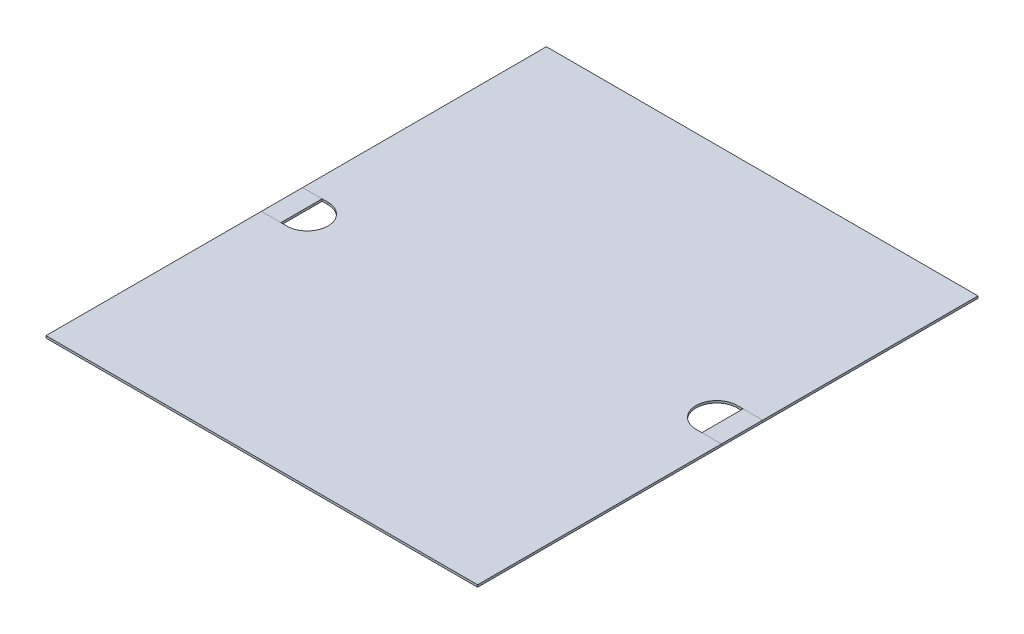
SolidWorks part; units mm, degrees
ref_plane "Front Plane" through (0, 0, 0) normal (0, 0, 1) x (1, 0, 0)
ref_plane "Top Plane" through (0, 0, 0) normal (0, 1, 0) x (1, 0, 0)
ref_plane "Right Plane" through (0, 0, 0) normal (1, 0, 0) x (0, 0, -1)
sketch "Sketch1" plane through (0, 0, 0) normal (0, 1, 0) x (1, 0, 0)
  line L1 (0, 0) -> (199, 0)
  line L3 (0, 230.7) -> (199, 230.7)
  line L5 (11.75, 118.25) -> (0.0406, 118.25)
  line L6 (11.75, 99.25) -> (0.0406, 99.25)
  line L8 (0.0406, 118.25) -> (0, 230.7)
  line L9 (0.0406, 99.25) -> (0, 0)
  line L10 (99.5, 230.7) -> (99.5, 0) construction
  line L11 (187.25, 99.25) -> (198.9594, 99.25) construction
  line L12 (187.25, 118.25) -> (198.9594, 118.25) construction
  line L13 (199, 115.35) -> (0.0406, 115.35) construction
  line L14 (187.25, 131.45) -> (198.9594, 131.45)
  line L15 (187.25, 112.45) -> (198.9594, 112.45)
  line L16 (199, 230.7) -> (198.9594, 131.45)
  line L17 (198.9594, 112.45) -> (199, 0)
  arc A1 (11.75, 99.25) -> (11.75, 118.25) centre (11.75, 108.75) ccw
  arc A2 (187.25, 99.25) -> (187.25, 118.25) centre (187.25, 108.75) cw construction
  arc A3 (187.25, 131.45) -> (187.25, 112.45) centre (187.25, 121.95) ccw
  dimension "D4" = 19
  dimension "D1" = 199
  dimension "D2" = 230.7
  dimension "D5" = 108.75
extrude "Boss-Extrude1" add sketch "Sketch1" along normal blind 1
sketch "Sketch2" plane through (0, 1, 0) normal (0, 1, 0) x (1, 0, 0)
  line L0 (11.75, 99.25) -> (0.0406, 99.25) construction
  line L1 (0.0406, 118.25) -> (9.0406, 118.25)
  line L2 (0.0406, 118.25) -> (0.0406, 99.25)
  line L3 (0.0406, 99.25) -> (9.0406, 99.25)
  line L4 (9.0406, 118.25) -> (9.0406, 99.25)
  line L5 (0.0406, 118.25) -> (9.0406, 99.25) construction
  line L6 (0.0406, 99.25) -> (9.0406, 118.25) construction
  line L7 (198.9594, 112.45) -> (187.25, 112.45) construction
  line L8 (198.9594, 131.45) -> (189.9594, 131.45)
  line L9 (198.9594, 131.45) -> (198.9594, 112.45)
  line L10 (198.9594, 112.45) -> (189.9594, 112.45)
  line L11 (189.9594, 131.45) -> (189.9594, 112.45)
  line L12 (198.9594, 131.45) -> (189.9594, 112.45) construction
  line L13 (198.9594, 112.45) -> (189.9594, 131.45) construction
  point P4 (4.5406, 108.75)
  point P12 (194.4594, 121.95)
  dimension "D1" = 9
  dimension "D2" = 9
extrude "Boss-Extrude2" add sketch "Sketch2" against normal through all separate body
